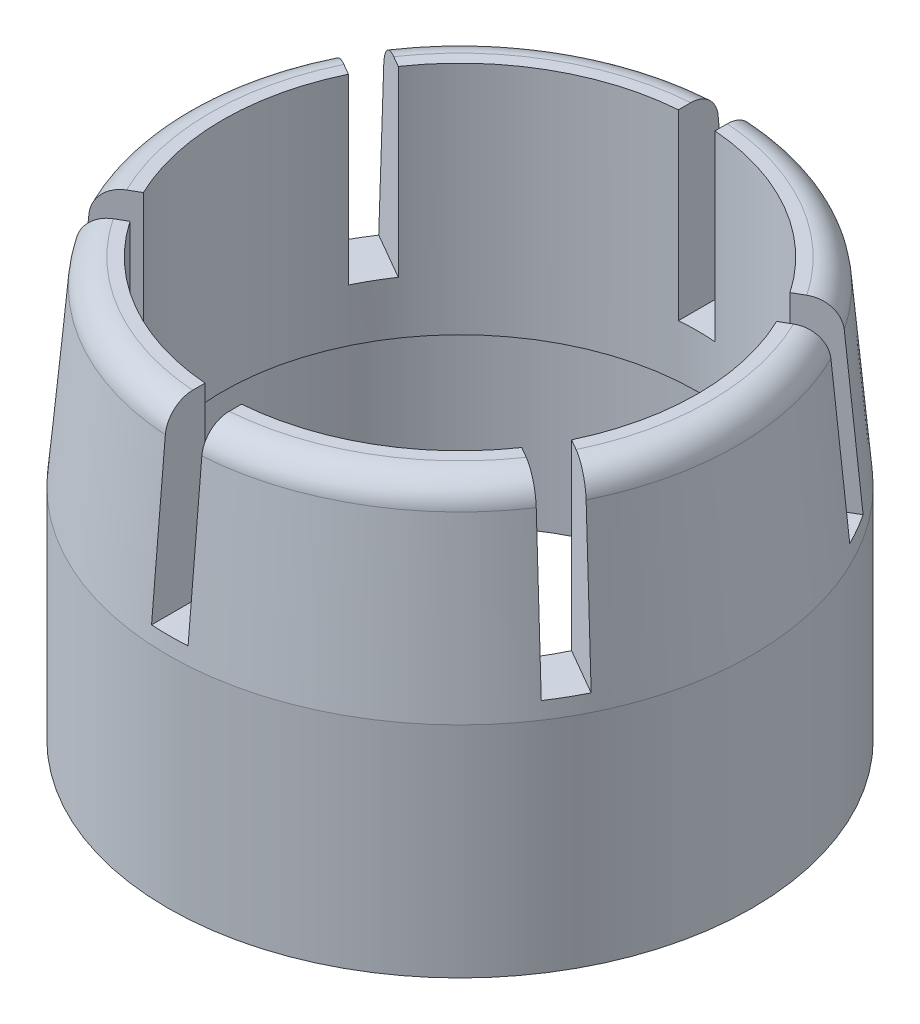
SolidWorks part; units mm, degrees
ref_plane "Front Plane" through (0, 0, 0) normal (0, 0, 1) x (1, 0, 0)
ref_plane "Top Plane" through (0, 0, 0) normal (0, 1, 0) x (1, 0, 0)
ref_plane "Right Plane" through (0, 0, 0) normal (1, 0, 0) x (0, 0, -1)
sketch "Sketch1" plane through (0, 0, 0) normal (0, 0, 1) x (1, 0, 0)
  line L0 (0, 0) -> (0, 10.854) construction
  line L1 (14.3, -2.9731) -> (16, -2.9731) construction
  line L2 (14.3, -2.9731) -> (16, -2.9731)
  line L8 (14.3, 7.0269) -> (14.3, -2.9731)
  line L11 (16, -2.9731) -> (16, 9.0269)
  line L13 (13, 19.9069) -> (13.6757, 19.9069)
  line L14 (15.17, 18.5374) -> (16, 9.0269)
  line L15 (13, 19.9069) -> (13, 7.0269)
  line L16 (13, 7.0269) -> (14.3, 7.0269)
  arc A0 (15.17, 18.5374) -> (13.6757, 19.9069) centre (13.6757, 18.4069) ccw
  point P12 (13.6757, 19.6671)
  point P13 (9.65, 6.878)
  point P14 (0, 0)
  point P15 (9.65, 7.0293)
  point P16 (13, 7.0269)
  point P17 (0, 0)
  dimension "D8" = 1.5
  dimension "D1" = 14.3
  dimension "D2" = 13
  dimension "D3" = 10
  dimension "D4" = 22.88
  dimension "D5" = 12
  dimension "D7" = 16
revolve "Revolve1" add sketch "Sketch1" angle 360 about L0
sketch "Sketch3" plane through (0, 19.9069, 0) normal (0, 1, 0) x (1, 0, 0)
  line L0 (0, 0) -> (0, 13.8007) construction
  line L2 (-1, 8.3651) -> (1, 8.3651)
  line L3 (-1, 8.3651) -> (-1, 18.9862)
  line L4 (-1, 18.9862) -> (1, 18.9862)
  line L5 (1, 8.3651) -> (1, 18.9862)
  line L6 (-1, 8.3651) -> (1, 18.9862) construction
  line L7 (-1, 18.9862) -> (1, 8.3651) construction
  circle A0 centre (0, 0) radius 13.6757 construction
  point P3 (0, 13.6757)
  dimension "D1" = 2
extrude "Cut-Extrude1" cut sketch "Sketch3" against normal blind 10
pattern_circular "CirPattern1" count 6 every 60 about axis through (0, 0, 0) along (0, 1, 0) of "Cut-Extrude1"
